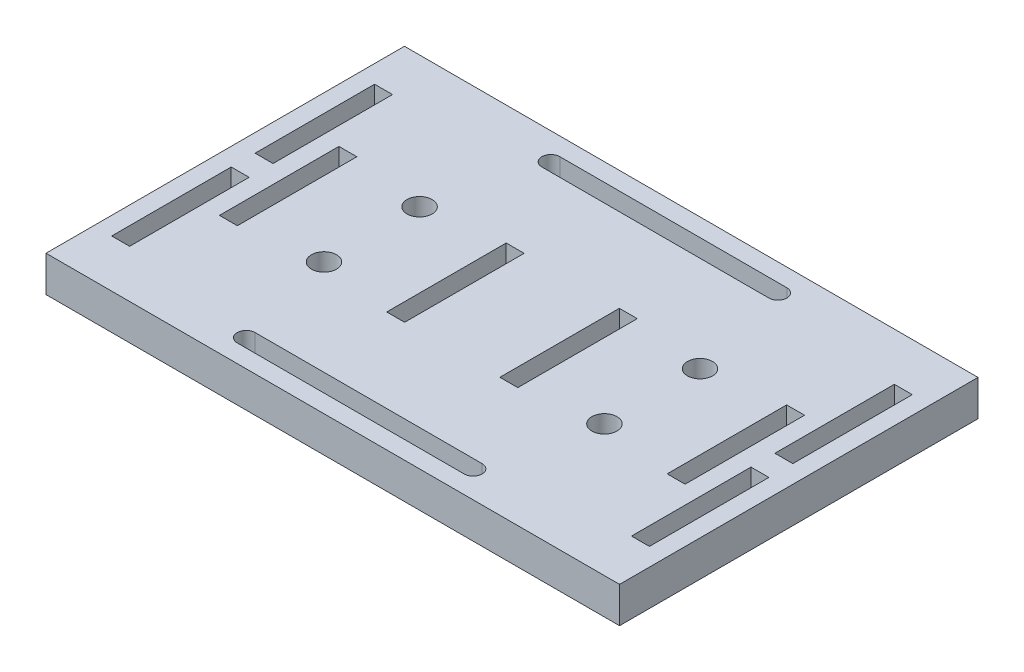
SolidWorks part; units mm, degrees
ref_plane "前视基准面" through (0, 0, 0) normal (0, 0, 1) x (1, 0, 0)
ref_plane "上视基准面" through (0, 0, 0) normal (0, 1, 0) x (1, 0, 0)
ref_plane "右视基准面" through (0, 0, 0) normal (1, 0, 0) x (0, 0, -1)
other "Configuration Table"
sketch "草图1" plane through (0, 0, 0) normal (0, 1, 0) x (1, 0, 0)
  line L0 (53.5, 0) -> (53.5, -60)
  line L9 (5.5, 0) -> (101.5, 0)
  line L22 (8.5, -32) -> (11.5, -32)
  line L23 (8.5, -8) -> (11.5, -8)
  line L24 (8.5, -8) -> (8.5, -28)
  line L25 (8.5, -28) -> (11.5, -28)
  line L26 (11.5, -8) -> (11.5, -28)
  line L27 (11.5, -52) -> (11.5, -32)
  line L28 (8.5, -52) -> (11.5, -52)
  line L29 (8.5, -52) -> (8.5, -32)
  line L30 (98.5, -28) -> (95.5, -28)
  line L31 (95.5, -8) -> (95.5, -28)
  line L32 (98.5, -8) -> (95.5, -8)
  line L33 (98.5, -8) -> (98.5, -28)
  line L34 (98.5, -52) -> (98.5, -32)
  line L35 (98.5, -52) -> (95.5, -52)
  line L36 (95.5, -52) -> (95.5, -32)
  line L37 (98.5, -32) -> (95.5, -32)
  line L38 (5.5, 0) -> (5.5, -60)
  line L39 (101.5, 0) -> (101.5, -60)
  line L40 (101.5, -60) -> (5.5, -60)
  line L41 (92.4695, -40) -> (89.4695, -40)
  line L42 (14.5305, -20) -> (17.5305, -20)
  line L43 (14.5305, -20) -> (14.5305, -40)
  line L44 (14.5305, -40) -> (17.5305, -40)
  line L45 (17.5305, -20) -> (17.5305, -40)
  line L46 (89.4695, -20) -> (89.4695, -40)
  line L47 (92.4695, -20) -> (89.4695, -20)
  line L48 (92.4695, -20) -> (92.4695, -40)
  line L49 (34.5, -54) -> (72.5, -54)
  line L50 (34.5, -6) -> (72.5, -6)
  line L51 (72.5, -3) -> (34.5, -3)
  line L52 (34.5, -57) -> (72.5, -57)
  line L53 (64.4695, -40) -> (61.4695, -40)
  line L54 (42.5305, -20) -> (45.5305, -20)
  line L55 (42.5305, -20) -> (42.5305, -40)
  line L56 (42.5305, -40) -> (45.5305, -40)
  line L57 (45.5305, -20) -> (45.5305, -40)
  line L58 (61.4695, -20) -> (61.4695, -40)
  line L59 (64.4695, -20) -> (61.4695, -20)
  line L60 (64.4695, -20) -> (64.4695, -40)
  line L61 (17.5305, -30) -> (42.5305, -30)
  circle A0 centre (72.5, -4.5) radius 1.5
  circle A1 centre (34.5, -4.5) radius 1.5
  circle A2 centre (72.5, -55.5) radius 1.5
  circle A3 centre (34.5, -55.5) radius 1.5
  circle A4 centre (30.0305, -38) radius 2.1
  circle A5 centre (30.0305, -22) radius 2.1
  circle A6 centre (76.9695, -38) radius 2.1
  circle A7 centre (76.9695, -22) radius 2.1
  dimension "D10" = 3
  dimension "D11" = 19
  dimension "D12" = 25
  dimension "D13" = 3
  dimension "D14" = 4.2
  dimension "D15" = 12.5
  dimension "D2" = 3
  dimension "D3" = 20
  dimension "D4" = 8
  dimension "D5" = 96
  dimension "D6" = 20
  dimension "D7" = 3
  dimension "D8" = 20
  dimension "D9" = 3
  dimension "D16" = 8
extrude "凸台-拉伸1" add sketch "草图1" along normal blind 6 contours A3 L49 L0 L50 A1 L51 L9 L38 L40 L52 L23 L26 L25 L24 L28 L29 L22 L27 L42 L45 L44 L43 | L49 A2 L52 L0 L40 L39 L9 L51 A0 L50 L32 L33 L30 L31 L37 L34 L35 L36 L47 L48 L41 L46
